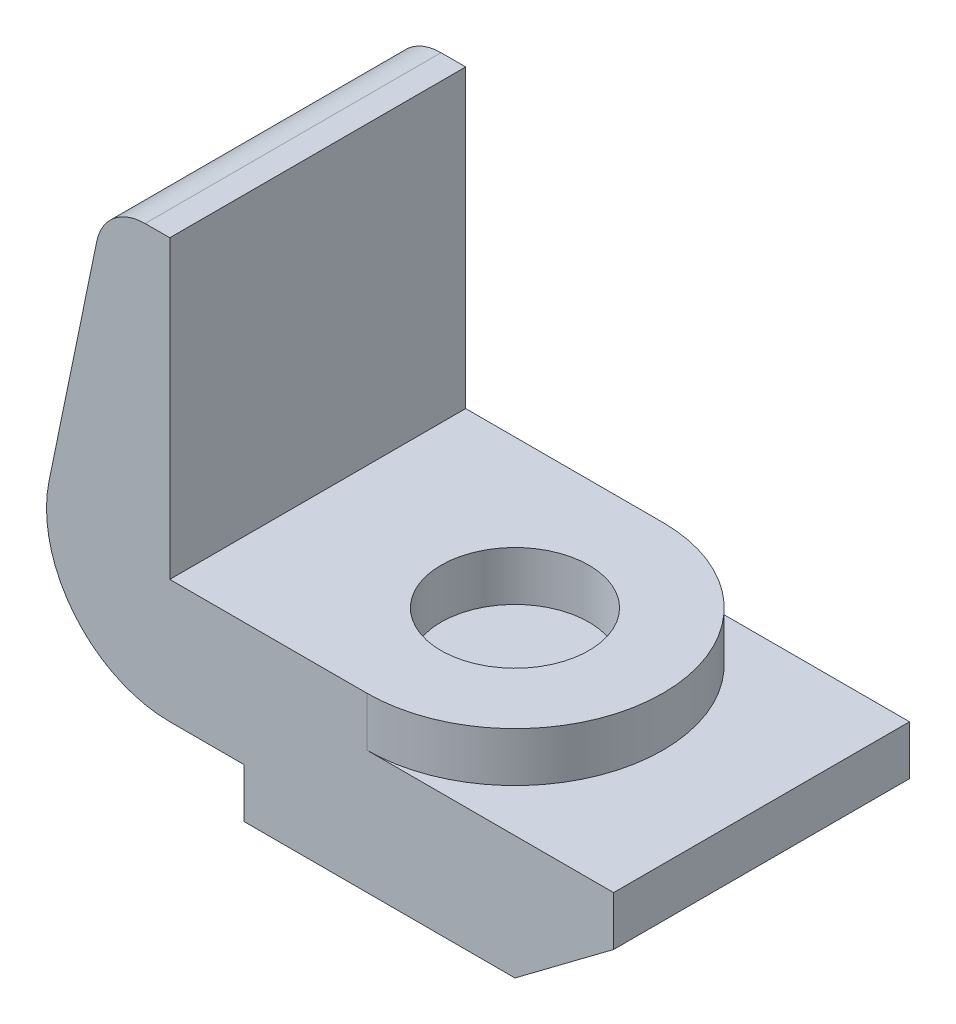
SolidWorks part; units mm, degrees
ref_plane "Front Plane" through (0, 0, 0) normal (0, 0, 1) x (1, 0, 0)
ref_plane "Top Plane" through (0, 0, 0) normal (0, 1, 0) x (1, 0, 0)
ref_plane "Right Plane" through (0, 0, 0) normal (1, 0, 0) x (0, 0, -1)
sketch "Sketch1" plane through (0, 0, 0) normal (0, 0, 1) x (1, 0, 0)
  line L0 (0, 0) -> (69.85, 0)
  line L1 (69.85, 0) -> (95.25, 19.05)
  line L2 (95.25, 19.05) -> (95.25, 31.75)
  line L3 (95.25, 31.75) -> (31.75, 31.75)
  line L4 (31.75, 31.75) -> (31.75, 44.45)
  line L5 (31.75, 44.45) -> (-19.05, 44.45)
  line L6 (-19.05, 44.45) -> (-19.05, 120.65)
  line L7 (0, 0) -> (0, 12.7)
  line L8 (0, 12.7) -> (-19.05, 12.7)
  line L9 (-19.05, 120.65) -> (-25.4, 120.65)
  line L10 (-37.838, 110.5162) -> (-50.1451, 50.8655)
  arc A3 (-50.1451, 50.8655) -> (-19.05, 12.7) centre (-19.05, 44.45) ccw
  arc A5 (-25.4, 120.65) -> (-37.838, 110.5162) centre (-25.4, 107.95) ccw
  dimension "D9" = 6.35
  dimension "D10" = 25.4
  dimension "D11" = 120.65
  dimension "D1" = 69.85
  dimension "D2" = 12.7
  dimension "D3" = 12.7
  dimension "D4" = 50.8
  dimension "D5" = 19.05
  dimension "D6" = 31.75
  dimension "D7" = 44.45
  dimension "D8" = 114.3
extrude "Boss-Extrude1" add sketch "Sketch1" along normal blind 76.2
sketch "Sketch3" plane through (0, 31.75, 0) normal (0, 1, 0) x (1, 0, 0)
  line L0 (31.75, -76.2) -> (31.75, 0) construction
  circle A0 centre (31.75, -38.1) radius 38.1
extrude "Boss-Extrude2" add sketch "Sketch3" along normal up to surface (12.7 mm away) up to face at (6.35, 44.45, 38.1)
sketch "Sketch4" plane through (0, 44.45, 0) normal (0, 1, 0) x (1, 0, 0)
  circle A0 centre (31.75, -38.1) radius 19.05
  dimension "D1" = 38.1
extrude "Cut-Extrude1" cut sketch "Sketch4" against normal blind 12.7
